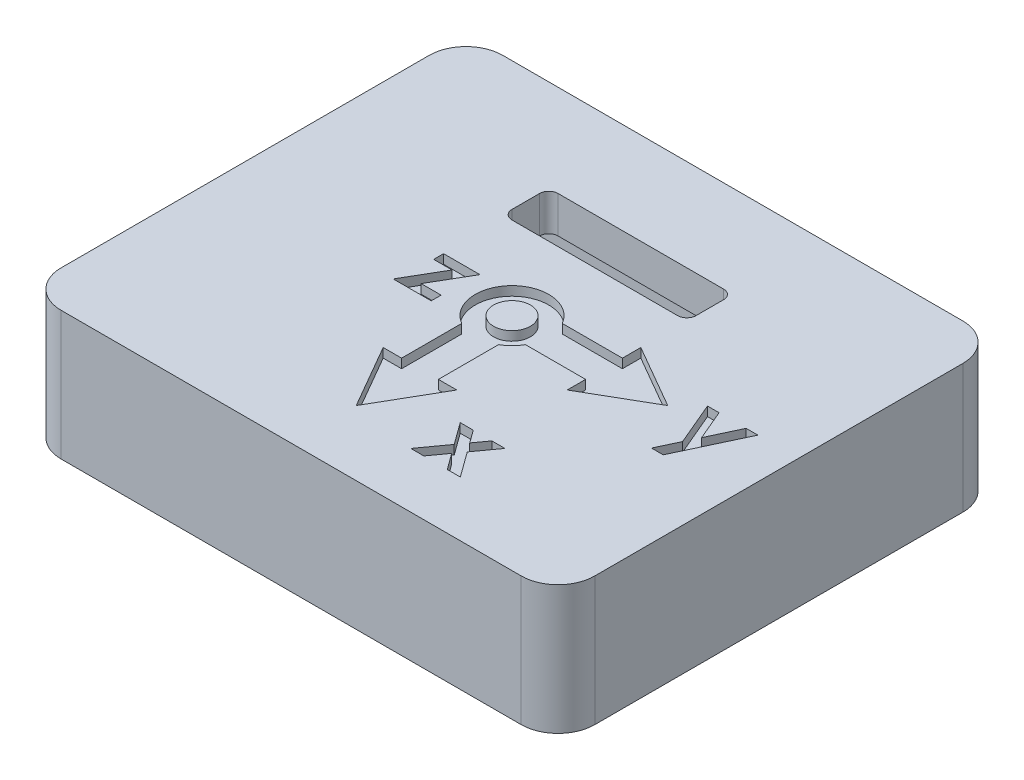
SolidWorks part; units mm, degrees
ref_plane "Front Plane" through (0, 0, 0) normal (0, 0, 1) x (1, 0, 0)
ref_plane "Top Plane" through (0, 0, 0) normal (0, 1, 0) x (1, 0, 0)
ref_plane "Right Plane" through (0, 0, 0) normal (1, 0, 0) x (0, 0, -1)
sketch "Sketch1" plane through (0, 0, 0) normal (0, 1, 0) x (1, 0, 0)
  line L1 (-14.5, -12) -> (14.5, -12)
  line L2 (-14.5, -12) -> (-14.5, 12)
  line L3 (-14.5, 12) -> (14.5, 12)
  line L4 (14.5, -12) -> (14.5, 12)
  line L5 (-14.5, -12) -> (14.5, 12) construction
  line L6 (-14.5, 12) -> (14.5, -12) construction
  point P0 (0, 0)
  point P6 (0, 0)
  dimension "D1" = 29
  dimension "D2" = 24
extrude "Boss-Extrude1" add sketch "Sketch1" along normal blind 2
sketch "Sketch2" plane through (0, 0, 0) normal (0, -1, 0) x (1, 0, 0)
  line L0 (-14.5, 12) -> (14.5, 12) construction
  line L1 (-12.5, -10) -> (12.5, -10)
  line L2 (-12.5, -10) -> (-12.5, 10)
  line L3 (-12.5, 10) -> (12.5, 10)
  line L4 (12.5, -10) -> (12.5, 10)
  line L5 (-12.5, -10) -> (12.5, 10) construction
  line L6 (-12.5, 10) -> (12.5, -10) construction
  line L7 (-14.5, -12) -> (-14.5, 12) construction
  line L8 (-14.5, 12) -> (14.5, 12)
  line L9 (14.5, 12) -> (14.5, -12)
  line L10 (14.5, -12) -> (-14.5, -12)
  line L11 (-14.5, -12) -> (-14.5, 12)
  point P0 (0, 0)
  dimension "D1" = 2
  dimension "D2" = 2
extrude "Boss-Extrude2" add sketch "Sketch2" along normal blind 5
sketch "Sketch3" plane through (0, 2, 0) normal (0, 1, 0) x (1, 0, 0)
  line L0 (-14.5, 7) -> (14.5, 7) construction
  line L1 (-14.5, 12) -> (-14.5, -12) construction
  line L2 (14.5, -12) -> (14.5, 12) construction
  line L3 (14.5, 12) -> (-14.5, 12) construction
  line L4 (-14.5, 4.5) -> (14.5, 4.5) construction
  line L6 (-5, 4.5) -> (5, 4.5)
  line L7 (-5, 4.5) -> (-5, 7)
  line L8 (-5, 7) -> (5, 7)
  line L9 (5, 4.5) -> (5, 7)
  point P14 (-5, 5.75)
  dimension "D1" = 5
  dimension "D2" = 2.5
  dimension "D3" = 10
  dimension "D4" = 5
extrude "Cut-Extrude1" cut sketch "Sketch3" against normal up to surface (2 mm away) up to face at (0, 0, 0)
sketch "Sketch7" plane through (0, 2, 0) normal (0, 1, 0) x (1, 0, 0)
  line L0 (0, 12) -> (0, -12) construction
  line L3 (14.5, 12) -> (-14.5, 12) construction
  line L4 (-14.5, -12) -> (14.5, -12) construction
  line L5 (-14.5, 0) -> (14.5, 0) construction
  line L6 (-14.5, 12) -> (-14.5, -12) construction
  line L7 (14.5, -12) -> (14.5, 12) construction
  line L8 (5, 2) -> (5, -2) construction
  line L9 (0, -1) -> (5, -1) construction
  line L10 (0, -1) -> (0, 1) construction
  line L11 (0, 1) -> (5, 1) construction
  line L12 (5, -1) -> (5, 1) construction
  line L13 (-1, 0) -> (1, 0) construction
  line L14 (-1, 0) -> (-1, -5) construction
  line L15 (-1, -5) -> (1, -5) construction
  line L16 (1, 0) -> (1, -5) construction
  line L17 (5, -2) -> (8.4641, 0)
  line L18 (8.4641, 0) -> (5, 2)
  line L19 (2, -5) -> (-2, -5) construction
  line L20 (-2, -5) -> (0, -8.4641)
  line L21 (0, -8.4641) -> (2, -5)
  line L22 (5, 2) -> (5, 1)
  line L23 (5, 1) -> (1.7321, 1)
  line L24 (-1, -1.7321) -> (-1, -5)
  line L25 (-1, -5) -> (-2, -5)
  line L26 (1, -1.7321) -> (1, -5)
  line L27 (1, -5) -> (2, -5)
  line L28 (1.7321, -1) -> (5, -1)
  line L29 (5, -1) -> (5, -2)
  circle A0 centre (0, 0) radius 2 construction
  arc A1 (1.7321, 1) -> (-1, -1.7321) centre (0, 0) ccw
  arc A2 (1, -1.7321) -> (1.7321, -1) centre (0, 0) ccw
  circle A3 centre (0, 0) radius 1
  point P35 (0, 0)
  point P36 (-9.7697, 1)
  point P37 (-11.1257, 1)
  dimension "D1" = 4
  dimension "D12" = 2
  dimension "D13" = 2
  dimension "D2" = 2
  dimension "D3" = 2
  dimension "D4" = 5
  dimension "D5" = 5
  dimension "D6" = 4
  dimension "D7" = 4
  dimension "D8" = 4
  dimension "D9" = 4
  dimension "D10" = 4
  dimension "D11" = 4
extrude "Cut-Extrude2" cut sketch "Sketch7" against normal blind 0.5 contours L29 L17 L18 L22 L23 A1 L24 L25 L20 L21 L27 L26 A2 L28 | A3
sketch "Sketch10" plane through (0, 2, 0) normal (0, 1, 0) x (1, 0, 0)
  line L0 (-14.5, -12) -> (14.5, -12) construction
  line L1 (14.5, -12) -> (14.5, 12) construction
  text T0 "<b>y</b>"
  text T1 "<b>x</b>"
  text T2 "<b>z</b>"
  point P9 (-14, -6.8825)
  dimension "D1" = 10.5
  dimension "D2" = 5
  dimension "D3" = 3
  dimension "D4" = 11
  dimension "D5" = 14.5
  dimension "D6" = 10.5
extrude "Cut-Extrude4" cut sketch "Sketch10" against normal blind 0.5
fillet "Fillet3" radius 2 8 edges at (-14.5, -1.5, -12) (14.5, -1.5, -12) (14.5, -1.5, 12) (-14.5, -1.5, 12) (12.5, -2.5, -10) (-12.5, -2.5, -10) (-12.5, -2.5, 10) (12.5, -2.5, 10)
fillet "Fillet4" radius 0.5 4 edges at (5, 1, -7) (5, 1, -4.5) (-5, 1, -4.5) (-5, 1, -7)
